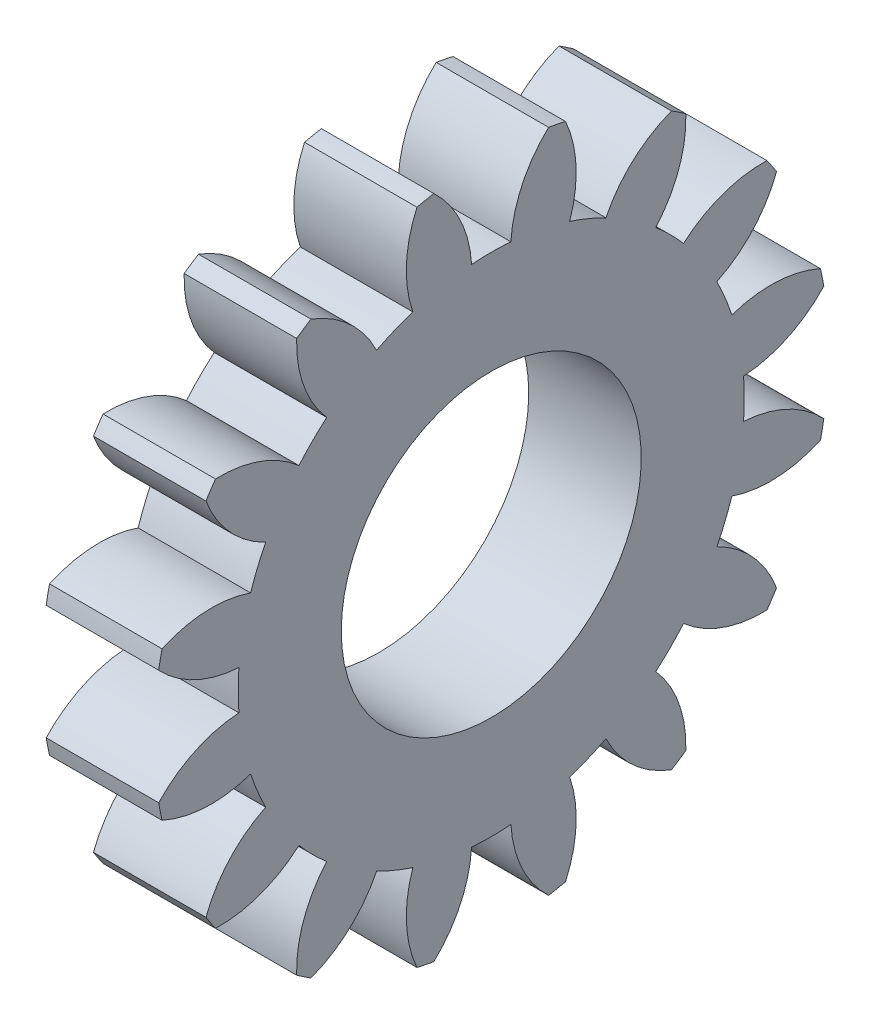
SolidWorks part; units mm, degrees
ref_plane "Plane1" through (0, 0, 0) normal (0, 0, 1) x (1, 0, 0)
ref_plane "Plane2" through (0, 0, 0) normal (0, 1, 0) x (1, 0, 0)
ref_plane "Plane3" through (0, 0, 0) normal (1, 0, 0) x (0, 0, -1)
sketch "HoldingSke" plane through (0, 0, 0) normal (0, 1, 0) x (1, 0, 0)
  line L0 (0, 0) -> (0.9613, -0.2756)
  line L1 (-15, 0) -> (100, 0) construction
  line L2 (0, 0) -> (-2.1039, 2.3779)
  line L3 (0, 0) -> (-11.863, 4.5341)
  line L4 (0, 0) -> (8.3015, 2.3804)
  line L5 (0, 0) -> (-46.8476, -17.4728)
  line L6 (0, 0) -> (-2.4869, -1.6779)
  line L7 (-2.1039, 2.3779) -> (8.6586, 51.2059)
  line L8 (-76.2, 54.61) -> (-74.8, 54.61)
  line L9 (-71.009, 38.7566) -> (-53.1078, 45.2721)
  line L10 (-76.2, 71.12) -> (104.1128, 71.12)
  line L11 (0, 0) -> (-3, 0)
  line L12 (-76.2, 101.6) -> (-76.162, 101.6)
  line L13 (24.9733, 27.94) -> (52.9518, 28.4284)
  line L14 (24.9733, 27.94) -> (24.9743, 27.94)
  line L15 (24.9733, 27.94) -> (100.4006, 29.5858)
  line L16 (-63.627, -1) -> (-12.827, -1)
  circle A0 centre (0, 0) radius 4
  circle A1 centre (0, 0) radius 6.749
  circle A2 centre (0, 0) radius 37.5
  circle A3 centre (0, 0) radius 4
  dimension "MHD" = 13.498
  dimension "Hub_dia" = 75
  dimension "Bore" = 8
  dimension "MBD" = 8
  dimension "Num_teeth" = 16
  dimension "Pitch" = 1
  dimension "Overall_len" = 50
  dimension "Show_teeth" = 16
  dimension "Thickness" = 3
  dimension "OAL" = 50.0001
  dimension "T_dim" = 1.4
  dimension "Ap" = 20
  dimension "H" = 19.05
  dimension "Pitch_radius" = 180.3128
  dimension "Width" = 3
  dimension "Backlash" = 0.038
  dimension "Addendum_fac" = 1
  dimension "Dedendum_fac" = 1.25
  dimension "Clearance_fac" = 0.25
  dimension "Dedendum_add" = 0.001
  dimension "Module" = 1
sketch "BasProSke" plane through (0, 0, 0) normal (0, 1, 0) x (1, 0, 0)
  line L0 (-10, 0) -> (60, 0) construction
  line L1 (0, 0) -> (0, 9)
  line L2 (0, 0) -> (3, 0)
  line L3 (3, 0) -> (3, 9)
  line L4 (3, 9) -> (0, 9)
  dimension "Thickness" = 3
  dimension "Diameter" = 18
revolve "Base-Revolve" add sketch "BasProSke" angle 360 about L0
sketch "TooCutSke" plane through (0, 0, 0) normal (1, 0, 0) x (0, 0, -1)
  line L1 (0, 0) -> (0, 107) construction
  line L2 (0, 0) -> (-0.8506, 7.9547) construction
  line L3 (0, 0) -> (-3.1089, 15.6293) construction
  line L4 (-0.8506, 7.9547) -> (-1.5544, 7.8146) construction
  arc A0 (0.5238, 6.7286) -> (-0.5238, 6.7286) centre (0, 0) ccw
  arc A1 (1.5534, 8.8907) -> (-1.5534, 8.8907) centre (0, 0) ccw
  circle A2 centre (0, 0) radius 8 construction
  circle A3 centre (0, 0) radius 7.5175 construction
  arc A4 (-0.5238, 6.7286) -> (-1.5534, 8.8907) centre (-3.7179, 6.5338) ccw
  arc A5 (1.5534, 8.8907) -> (0.5238, 6.7286) centre (3.7179, 6.5338) ccw
  dimension "Root_dia" = 13.498
  dimension "Overcut_dia" = 18.0508
  dimension "Pitch_dia" = 16
  dimension "Base_dia" = 15.0351
  dimension "Flank_rad" = 3.2
  dimension "Half_ang" = 11.25
  dimension "Half_CT" = 0.7176
extrude "ToothCut" cut sketch "TooCutSke" along normal through all
fillet "Breaks" [suppressed] radius 0.02
fillet "RootFillets" [suppressed] radius 0.251
pattern_circular "TeethCuts" count 16 every 22.5 about axis through (-10, 0, 0) along (1, 0, 0) of "ToothCut", "RootFillets", "Breaks"
sketch "HubNeaOneSke" plane through (0, 0, 0) normal (-1, 0, 0) x (0, 0, 1)
  circle A0 centre (0, 0) radius 6.749
  dimension "Diameter" = 13.498
extrude "HubNearOne" [suppressed] add sketch "HubNeaOneSke" along normal blind 47.0001
sketch "HubNeaBotSke" plane through (0, 0, 0) normal (-1, 0, 0) x (0, 0, 1)
  circle A0 centre (0, 0) radius 6.749
  dimension "Diameter" = 13.498
extrude "HubNearBoth" [suppressed] add sketch "HubNeaBotSke" along normal blind 23.5
ref_plane "FarPln" through (3, 0, 0) normal (1, 0, 0) x (0, 0, -1)
sketch "HubFarSke" plane through (3, 0, 0) normal (1, 0, 0) x (0, 0, -1)
  circle A0 centre (0, 0) radius 6.749
  dimension "Diameter" = 13.498
extrude "HubFar" [suppressed] add sketch "HubFarSke" along normal blind 23.5
sketch "BorSke" plane through (0, 0, 0) normal (1, 0, 0) x (0, 0, -1)
  circle A0 centre (0, 0) radius 4
  dimension "Diameter" = 8
extrude "Bore" cut sketch "BorSke" along normal mid plane 100.0001
sketch "KeySke" plane through (0, 0, 0) normal (1, 0, 0) x (0, 0, -1)
  line L0 (-1.5, 0) -> (-1.5, 5.4)
  line L1 (-1.5, 5.4) -> (1.5, 5.4)
  line L2 (1.5, 5.4) -> (1.5, 0)
  line L3 (0, 0) -> (0, 34) construction
  line L4 (-1.5, 0) -> (1.5, 0)
  dimension "Width" = 3
  dimension "Offset" = 5.4
extrude "Keyway" [suppressed] cut sketch "KeySke" along normal mid plane 100.0001
pattern_circular "Keyway2" [suppressed] count 2 every 90 about axis through (-10, 0, 0) along (1, 0, 0)
equation "' \"Module@HoldingSke\" = 6.35"
equation "' \"Num_teeth@HoldingSke\" = 12"
equation "' \"Ap@HoldingSke\" =  20"
equation "' \"Ap@HoldingSke\" = 20"
equation "' \"Width@HoldingSke\" = 0.5 * 25.4"
equation "' \"Hub_dia@HoldingSke\"= 1 * 25.4"
equation "' \"Hub_dia@HoldingSke\" = 1 * 25.4"
equation "' \"Overall_len@HoldingSke\" = 1.0 * 25.4"
equation "' \"Bore@HoldingSke\" = 0.75 * 25.4"
equation "' \"T_dim@HoldingSke\" = 0.1 * 25.4"
equation "' \"Width@KeySke\" = 0.25 * 25.4"
equation "' \"Show_teeth@HoldingSke\" = 13"
equation "' \"Backlash@HoldingSke\" = 0.009 * 25.4"
equation "' \"Addendum_fac@HoldingSke\" = 1.0"
equation "' \"Dedendum_fac@HoldingSke\" = 1.25"
equation "' \"Dedendum_add@HoldingSke\" = 0.00005 * 25.4"
equation "' \"Clearance_fac@HoldingSke\" = 0.25"
equation "\"Pitch@HoldingSke\" = 1 / \"Module@HoldingSke\""
equation "\"Overcut_dia@TooCutSke\" = (\"Num_teeth@HoldingSke\" + 2 * \"Addendum_fac@HoldingSke\") / \"Pitch@HoldingSke\" + 0.002 * 25.4"
equation "\"Pitch_dia@TooCutSke\" = \"Num_teeth@HoldingSke\" / \"Pitch@HoldingSke\""
equation "\"Base_dia@TooCutSke\" = \"Num_teeth@HoldingSke\" / \"Pitch@HoldingSke\" * cos((\"Ap@HoldingSke\"  * 3.14159265 / 180))"
equation "\"Root_dia@TooCutSke\" = (\"Num_teeth@HoldingSke\" + 2) / \"Pitch@HoldingSke\" - 2 * (\"Addendum_fac@HoldingSke\" + \"Dedendum_fac@HoldingSke\") / \"Pitch@HoldingSke\" - \"Dedendum_add@HoldingSke\" * 2"
equation "\"Half_ang@TooCutSke\" = 180 / \"Num_teeth@HoldingSke\""
equation "\"Half_CT@TooCutSke\" = \"Num_teeth@HoldingSke\" / \"Pitch@HoldingSke\" * sin((3.14159265 / 2 / \"Num_teeth@HoldingSke\")) / 2 - 7 * \"Backlash@HoldingSke\" / 4"
equation "\"Flank_rad@TooCutSke\" = \"Num_teeth@HoldingSke\" / \"Pitch@HoldingSke\" / 5"
equation "\"Radius@RootFillets\" = \"Clearance_fac@HoldingSke\" / \"Pitch@HoldingSke\" + \"Dedendum_add@HoldingSke\""
equation "\"Break_rad@Breaks\" = 0.02 / \"Pitch@HoldingSke\""
equation "\"Thickness@HoldingSke\" = \"Width@HoldingSke\""
equation "\"OAL@HoldingSke\" = \"Thickness@HoldingSke\""
equation "\"MHD@HoldingSke\" = (\"Num_teeth@HoldingSke\" + 2) / \"Pitch@HoldingSke\" - 2 * (\"Addendum_fac@HoldingSke\" + \"Dedendum_fac@HoldingSke\")  / \"Pitch@HoldingSke\" - \"Dedendum_add@HoldingSke\" * 2"
equation "\"MBD@HoldingSke\" = (\"Num_teeth@HoldingSke\" + 2) / \"Pitch@HoldingSke\" - 2 * (\"Addendum_fac@HoldingSke\" + \"Dedendum_fac@HoldingSke\")  / \"Pitch@HoldingSke\" - \"Dedendum_add@HoldingSke\" * 2 - 0.002 * 25.4"
equation "\"MHD@HoldingSke\" = ((sgn( \"MHD@HoldingSke\" - \"Hub_dia@HoldingSke\" )-1)*( \"MHD@HoldingSke\" - \"Hub_dia@HoldingSke\" ))/-2+ \"Hub_dia@HoldingSke\""
equation "\"MBD@HoldingSke\" = ((sgn( \"MBD@HoldingSke\" - \"Bore@HoldingSke\" )-1)*( \"MBD@HoldingSke\" - \"Bore@HoldingSke\" ))/-2+ \"Bore@HoldingSke\""
equation "\"OAL@HoldingSke\" = ((sgn( \"OAL@HoldingSke\" - \"Overall_len@HoldingSke\" )+1)*( \"OAL@HoldingSke\" - \"Overall_len@HoldingSke\" ))/2 + \"Overall_len@HoldingSke\" + 0.000002 * 25.4"
equation "\"Num_teeth@TeethCuts\" = int( \"Show_teeth@HoldingSke\" ) + 1"
equation "\"Num_teeth@TeethCuts\" = ((sgn( \"Num_teeth@TeethCuts\" - \"Num_teeth@HoldingSke\" )-1)*( \"Num_teeth@TeethCuts\" - \"Num_teeth@HoldingSke\" ))/-2+ \"Num_teeth@HoldingSke\""
equation "\"Num_teeth@TeethCuts\" = ((sgn( \"Num_teeth@TeethCuts\" - 2.0)+1)*( \"Num_teeth@TeethCuts\" - 2.0))/2 +2.0"
equation "\"Angle@TeethCuts\" = 360.0 / \"Num_teeth@HoldingSke\""
equation "\"Diameter@BasProSke\" = (\"Num_teeth@HoldingSke\" + 2 * \"Addendum_fac@HoldingSke\") / \"Pitch@HoldingSke\""
equation "\"Thickness@BasProSke\"  = \"Thickness@HoldingSke\""
equation "' \"Fillet_rad@BasProSke\" =  \"Thickness@HoldingSke\" * 0.05"
equation "' \"Fillet_rad@BasProSke\" = \"Thickness@HoldingSke\" * 0.05"
equation "\"MHD@HoldingSke\" = ((sgn( \"MHD@HoldingSke\" - \"Root_dia@TooCutSke\" )-1)*( \"MHD@HoldingSke\" - \"Root_dia@TooCutSke\" ))/-2+ \"Root_dia@TooCutSke\""
equation "\"Diameter@HubNeaOneSke\" = \"MHD@HoldingSke\""
equation "\"Length@HubNearOne\" = \"OAL@HoldingSke\" - \"Thickness@BasProSke\""
equation "\"Diameter@HubNeaBotSke\" = \"MHD@HoldingSke\""
equation "\"Length@HubNearBoth\" = ( \"OAL@HoldingSke\" - \"Thickness@BasProSke\" ) / 2.0"
equation "\"Thickness@FarPln\" = \"Thickness@BasProSke\""
equation "\"Diameter@HubFarSke\" = \"MHD@HoldingSke\""
equation "\"Length@HubFar\" = ( \"OAL@HoldingSke\" - \"Thickness@BasProSke\" ) / 2.0"
equation "\"Diameter@BorSke\" = \"MBD@HoldingSke\""
equation "\"D1@Bore\" = \"OAL@HoldingSke\" * 2.0"
equation "\"D1@Keyway\" = \"OAL@HoldingSke\" * 2.0"
equation "\"Offset@KeySke\" = \"T_dim@HoldingSke\" + \"MBD@HoldingSke\" / 2.0"
